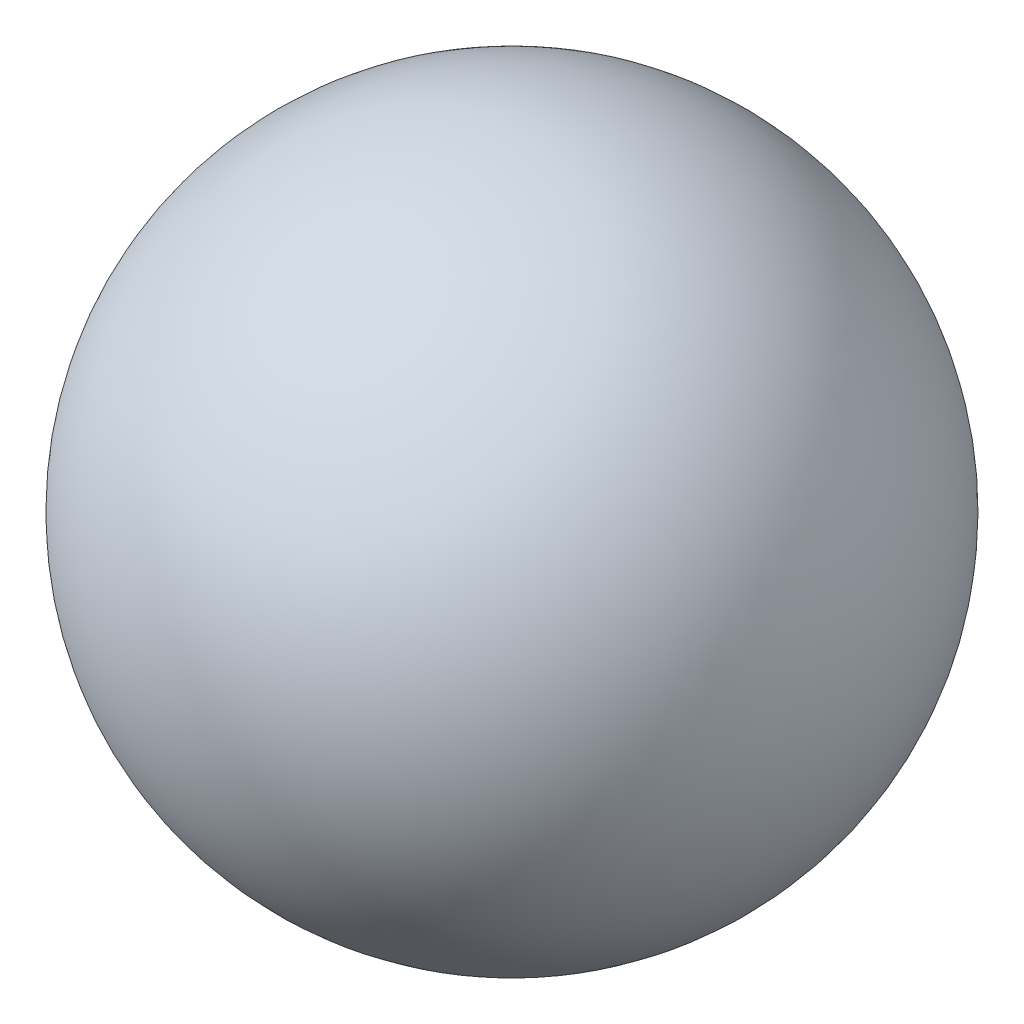
SolidWorks part; units mm, degrees
material "POM Ацеталь кополимер"
ref_plane "Спереди" through (0, 0, 0) normal (0, 0, 1) x (1, 0, 0)
ref_plane "Сверху" through (0, 0, 0) normal (0, 1, 0) x (1, 0, 0)
ref_plane "Справа" through (0, 0, 0) normal (1, 0, 0) x (0, 0, -1)
sketch "Эскиз1" plane through (0, 0, 0) normal (0, 0, 1) x (1, 0, 0)
  line L1 (0, 10) -> (0, 0)
  line L3 (0, 0) -> (0, -10)
  arc A0 (0, 10) -> (0, -10) centre (0, 0) cw
  dimension "D1" = 10
revolve "База" add sketch "Эскиз1" angle 360 about L1
sketch "Эскиз2" plane through (0, 0, 0) normal (0, 0, 1) x (1, 0, 0)
  line L1 (-6, -8.5) -> (6, -8.5)
  line L2 (-6, -8.5) -> (-6, -11.5)
  line L3 (-6, -11.5) -> (6, -11.5)
  line L4 (6, -8.5) -> (6, -11.5)
  point P4 (0, -8.5)
  dimension "D1" = 8.5
  dimension "D2" = 3
  dimension "D3" = 12
extrude "Вырез-Вытянуть1" cut sketch "Эскиз2" against normal mid plane 12
sketch "Эскиз3" plane through (0, -8.5, 0) normal (0, -1, 0) x (1, 0, 0)
  circle A0 centre (0, 0) radius 3
  dimension "D1" = 6
extrude "Вырез-Вытянуть2" cut sketch "Эскиз3" against normal blind 15
